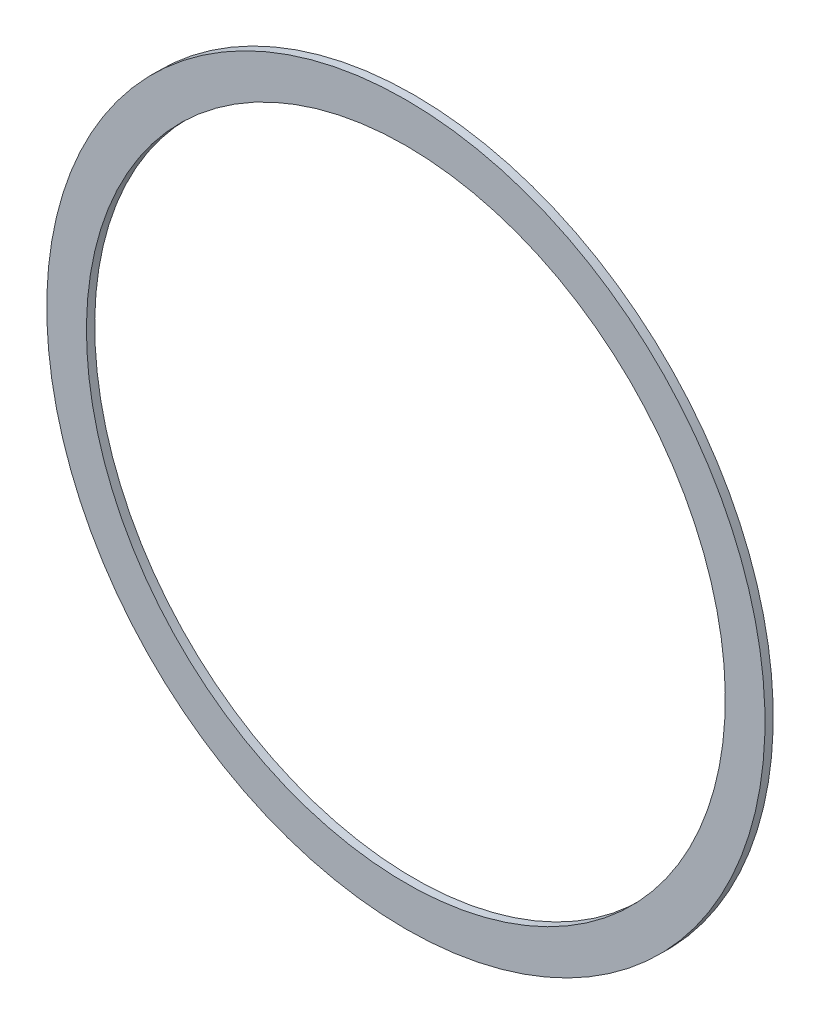
SolidWorks part; units mm, degrees
material "Balsa"
ref_plane "Front Plane" through (0, 0, 0) normal (0, 0, 1) x (1, 0, 0)
ref_plane "Top Plane" through (0, 0, 0) normal (0, 1, 0) x (1, 0, 0)
ref_plane "Right Plane" through (0, 0, 0) normal (1, 0, 0) x (0, 0, -1)
sketch "Sketch1" plane through (0, 0, 0) normal (0, 0, 1) x (1, 0, 0)
  line L0 (0, 0) -> (0, 499.9473) construction
  line L1 (0, -114.7984) -> (0, -129.4545) construction
  line L2 (0, -374.4718) -> (0, 404.2655) construction
  line L3 (-1.651, 142.9921) -> (-1.651, 150.6121) construction
  line L4 (1.651, 142.9921) -> (1.651, 150.6121) construction
  line L5 (-1.651, 142.9921) -> (1.651, 142.9921) construction
  line L6 (136.2041, -53.806) -> (0.0002, 24.7625) construction
  line L7 (-136.2076, -53.7991) -> (0.0002, 24.7625) construction
  line L8 (136.2041, -53.806) -> (0.0002, 24.7625) construction
  line L9 (-136.2076, -53.7991) -> (0.0002, 24.7625) construction
  line L10 (-125.0584, -45.4626) -> (-118.4576, -41.6554) construction
  line L11 (-123.6259, -48.4483) -> (-116.8078, -44.5157) construction
  line L12 (-118.4576, -41.6554) -> (-116.8078, -44.5157) construction
  line L13 (-124.1455, -48.7479) -> (-123.6847, -48.4822) construction
  line L14 (-123.6847, -48.4822) -> (-123.6259, -48.4483) construction
  line L15 (-125.7952, -45.8876) -> (-125.1113, -45.4931) construction
  line L16 (-125.1113, -45.4931) -> (-125.0584, -45.4626) construction
  line L17 (125.4797, -45.7137) -> (125.1075, -45.499) construction
  line L18 (123.8298, -48.5739) -> (123.6807, -48.488) construction
  line L19 (117.0223, -44.647) -> (118.6722, -41.7868) construction
  line L20 (123.6807, -48.488) -> (123.6228, -48.4545) construction
  line L21 (123.6228, -48.4545) -> (117.0223, -44.647) construction
  line L22 (125.1075, -45.499) -> (125.0554, -45.4689) construction
  line L23 (125.0554, -45.4689) -> (118.6722, -41.7868) construction
  line L24 (-107.079, -46.8884) -> (-120.3798, -54.5735)
  line L25 (-108.6638, -44.1348) -> (-121.9647, -51.8199)
  line L28 (-115.4206, -47.9666) -> (-121.9445, -51.7361) construction
  line L29 (-120.2754, -54.5131) -> (-108.646, -44.1245) construction
  line L30 (-114.4607, -49.3188) -> (-122.1124, -53.7399) construction
  line L31 (-113.7686, -50.8257) -> (-120.3665, -54.6379) construction
  line L32 (-115.4206, -47.9666) -> (-113.7686, -50.8257) construction
  line L33 (107.3025, -47.0245) -> (129.9098, -60.0883)
  line L34 (108.8884, -44.2715) -> (131.505, -57.3407)
  line L35 (129.9098, -60.0883) -> (131.505, -57.3407)
  line L36 (129.9098, -60.0883) -> (131.505, -57.3407) construction
  line L37 (108.8884, -44.2715) -> (131.505, -57.3407) construction
  line L38 (107.3025, -47.0245) -> (129.9098, -60.0883) construction
  line L39 (129.9098, -60.0883) -> (108.8884, -44.2715) construction
  line L40 (119.3991, -52.1799) -> (101.8722, -42.0519) construction
  line L41 (120.3631, -54.6438) -> (113.7655, -50.8313)
  line L42 (122.0152, -51.7848) -> (122.0057, -51.7794) construction
  line L43 (113.7655, -50.8313) -> (115.4176, -47.9723)
  line L44 (122.0057, -51.7794) -> (121.9413, -51.7421) construction
  line L45 (121.9413, -51.7421) -> (115.4176, -47.9723)
  line L46 (-108.6638, -44.1348) -> (-121.9647, -51.8199)
  line L47 (-107.079, -46.8884) -> (-120.3798, -54.5735)
  arc A0 (-1.651, 150.6121) -> (-125.0584, -45.4626) centre (0, 12.7) ccw
  circle A1 centre (0, 12.7) radius 120.904
  arc A2 (0, 150.622) -> (-1.651, 150.6121) centre (0, 12.7) ccw
  circle A3 centre (0, 12.7) radius 137.922 construction
  arc A4 (1.651, 150.6121) -> (0, 150.622) centre (0, 12.7) ccw
  arc A5 (-124.3508, -46.9604) -> (-123.6259, -48.4483) centre (0, 12.7) ccw
  arc A6 (-123.6259, -48.4483) -> (-121.9445, -51.7361) centre (0, 12.7) ccw
  arc A7 (-125.0584, -45.4626) -> (-124.3508, -46.9604) centre (0, 12.7) ccw
  arc A8 (124.3477, -46.9667) -> (125.0554, -45.4689) centre (0, 12.7) ccw
  arc A9 (125.0554, -45.4689) -> (1.651, 150.6121) centre (0, 12.7) ccw
  arc A10 (123.6228, -48.4545) -> (124.3477, -46.9667) centre (0, 12.7) ccw
  arc A11 (-121.9153, -51.7914) -> (-121.1641, -53.1919) centre (0, 12.7) ccw
  arc A12 (-120.3665, -54.6379) -> (120.3631, -54.6438) centre (0, 12.7) ccw
  arc A13 (-121.9445, -51.7361) -> (-121.9153, -51.7914) centre (0, 12.7) ccw
  arc A14 (-121.1641, -53.1919) -> (-120.3827, -54.6089) centre (0, 12.7) ccw
  arc A15 (-120.3827, -54.6089) -> (-120.397, -54.5834) centre (0, 12.7) ccw construction
  arc A16 (-120.397, -54.5834) -> (-120.3665, -54.6379) centre (0, 12.7) ccw construction
  arc A17 (120.3936, -54.5893) -> (121.0419, -53.416) centre (0, 12.7) ccw construction
  arc A18 (121.9413, -51.7421) -> (123.6228, -48.4545) centre (0, 12.7) ccw
  arc A19 (120.3631, -54.6438) -> (120.3936, -54.5893) centre (0, 12.7) ccw construction
  arc A20 (121.0419, -53.416) -> (121.9121, -51.7974) centre (0, 12.7) ccw construction
  arc A21 (121.9121, -51.7974) -> (121.9413, -51.7421) centre (0, 12.7) ccw construction
  spline S0 degree 3 poles (-891.8479, -1778.6566) (-223.5651, -622.3771) (442.5776, 534.0478) (1105.5233, 1688.7852) knots -629.037343 -629.037343 -629.037343 -629.037343 630.975162 630.975162 630.975162 630.975162 weights 1.000396 0.999868 0.999868 1.000397 only from (107.3025, -47.0245) to (108.8884, -44.2715)
  spline S1 degree 3 poles (-66.0123, 133.6164) (-70.0128, 131.4329) (-73.8716, 129.0699) (-81.3156, 123.9975) (-84.9009, 121.288) (-91.7995, 115.5249) (-95.113, 112.4712) (-99.0811, 108.4341) (-99.866, 107.6157) (-101.4182, 105.9565) (-102.1865, 105.1147) (-104.4569, 102.5643) (-105.9223, 100.8334) (-110.1768, 95.5512) (-115.4725, 88.2691) (-120.0285, 80.5179) (-123.1654, 74.5269) (-124.1643, 72.5002) (-125.5914, 69.415) (-126.0551, 68.3791) (-126.9587, 66.292) (-127.3989, 65.2397) (-129.5278, 59.9684) (-131.0098, 55.7) (-133.5456, 47.0638) (-134.5993, 42.696) (-136.2795, 33.8613) (-136.906, 29.3944) (-137.415, 23.7472) (-137.5031, 22.6146) (-137.6514, 20.3429) (-137.7116, 19.2049) (-137.8496, 15.7999) (-137.8852, 13.5361) (-137.8263, 6.7629) (-137.3062, -2.2197) (-135.9163, -11.1068) (-134.5433, -17.7359) (-134.0304, -19.9395) (-132.8922, -24.3345) (-132.2653, -26.5303) (-130.2347, -33.03) (-128.6774, -37.2656) (-126.1245, -43.2881) (-125.286, -45.1501) (-124.4066, -46.9926) knots 0 0 0 0 0.03125 0.03125 0.0625 0.0625 0.09375 0.09375 0.101563 0.101563 0.109375 0.109375 0.125 0.125 0.15625 0.1875 0.1875 0.203125 0.203125 0.210938 0.210938 0.21875 0.21875 0.25 0.25 0.28125 0.28125 0.3125 0.3125 0.320313 0.320313 0.328125 0.328125 0.34375 0.34375 0.375 0.40625 0.40625 0.421875 0.421875 0.4375 0.4375 0.46875 0.46875 0.48295 0.48295 0.48295 0.48295 construction
  spline S2 degree 3 poles (-1557.5256, 1030.3086) (-495.2142, -0.1753) (-82.1366, -210.7146) (81.4542, -98.9353) (85.033, -96.2237) (91.9188, -90.4573) (95.2258, -87.4025) (99.1858, -83.3647) (99.9691, -82.5461) (101.5182, -80.8868) (102.2849, -80.0449) (104.5506, -77.4941) (106.013, -75.7632) (110.2586, -70.4809) (112.9006, -66.8403) (117.8152, -59.3254) (120.0877, -55.4512) (123.2166, -49.4629) (124.2129, -47.4373) (125.6361, -44.3538) (126.0986, -43.3185) (126.9997, -41.2327) (127.4386, -40.181) (129.5618, -34.9121) (131.0396, -30.646) (133.5674, -22.0152) (134.6173, -17.6505) (136.2906, -8.8227) (136.914, -4.3596) (137.4197, 1.2823) (137.5071, 2.4139) (137.6542, 4.6834) (137.7138, 5.8206) (137.85, 9.2232) (137.8846, 11.4853) (137.8228, 18.2533) (137.2995, 27.2283) (135.9081, 36.1069) (134.5347, 42.7292) (134.0218, 44.9305) (132.8839, 49.3207) (132.2571, 51.5145) (130.2267, 58.0093) (128.67, 62.2416) (125.1615, 70.5162) (123.2097, 74.5586) (118.9108, 82.4534) (116.5637, 86.3058) (113.3753, 90.999) (112.7241, 91.9325) (111.3996, 93.7822) (110.7272, 94.697) (108.6802, 97.4113) (107.2757, 99.181) (102.9447, 104.3725) (96.8571, 110.9816) (90.1513, 116.9722) (84.8861, 121.2292) (83.0917, 122.6088) (80.3399, 124.6181) (79.4113, 125.2786) (77.543, 126.5731) (76.6028, 127.2075) (71.8708, 130.3161) (67.9881, 132.6004) (60.0328, 136.7739) (55.9603, 138.6631) (47.6249, 142.0446) (43.3619, 143.537) (37.9102, 145.1462) (36.8136, 145.4551) (34.6205, 146.0438) (33.5224, 146.3241) (30.2234, 147.1229) (28.0179, 147.5997) (21.3832, 148.8649) (16.9358, 149.4889) (7.993, 150.3014) (3.4975, 150.4899) (-3.2824, 150.4396) (-5.5486, 150.3672) (-10.0934, 150.1088) (-12.3559, 149.9236) (-19.101, 149.2046) (-23.5473, 148.5072) (-32.3412, 146.6856) (-36.6887, 145.5614) (-43.1354, 143.5526) (-45.2718, 142.8291) (-49.5193, 141.273) (-51.6323, 140.4395) (-274.1905, 46.1884) (-224.836, -608.7963) (101.1574, -1839.6029) knots -1.31339 -1.31339 -1.31339 -1.31339 0.03125 0.03125 0.0625 0.0625 0.09375 0.09375 0.101563 0.101563 0.109375 0.109375 0.125 0.125 0.15625 0.15625 0.1875 0.1875 0.203125 0.203125 0.210938 0.210938 0.21875 0.21875 0.25 0.25 0.28125 0.28125 0.3125 0.3125 0.320313 0.320313 0.328125 0.328125 0.34375 0.34375 0.375 0.40625 0.40625 0.421875 0.421875 0.4375 0.4375 0.46875 0.46875 0.5 0.5 0.53125 0.53125 0.539062 0.539062 0.546875 0.546875 0.5625 0.5625 0.59375 0.625 0.625 0.640625 0.640625 0.648437 0.648437 0.65625 0.65625 0.6875 0.6875 0.71875 0.71875 0.75 0.75 0.757812 0.757812 0.765625 0.765625 0.78125 0.78125 0.8125 0.8125 0.84375 0.84375 0.859375 0.859375 0.875 0.875 0.90625 0.90625 0.9375 0.9375 0.953125 0.953125 0.96875 0.96875 2.612134 2.612134 2.612134 2.612134 only from (66.1767, -108.566) to (-66.0123, 133.6164)
  spline S3 degree 3 poles (66.1767, -108.566) (70.1708, -106.3789) (74.0231, -104.0129) (81.4542, -98.9353) (85.033, -96.2237) (91.9188, -90.4573) (95.2258, -87.4025) (99.1858, -83.3647) (99.9691, -82.5461) (101.5182, -80.8868) (102.2849, -80.0449) (104.5506, -77.4941) (106.013, -75.7632) (110.2586, -70.4809) (112.9006, -66.8403) (117.8152, -59.3254) (120.0877, -55.4512) (123.2166, -49.4629) (124.2129, -47.4373) (125.6361, -44.3538) (126.0986, -43.3185) (126.9997, -41.2327) (127.4386, -40.181) (129.5618, -34.9121) (131.0396, -30.646) (133.5674, -22.0152) (134.6173, -17.6505) (136.2906, -8.8227) (136.914, -4.3596) (137.4197, 1.2823) (137.5071, 2.4139) (137.6542, 4.6834) (137.7138, 5.8206) (137.85, 9.2232) (137.8846, 11.4853) (137.8228, 18.2533) (137.2995, 27.2283) (135.9081, 36.1069) (134.5347, 42.7292) (134.0218, 44.9305) (132.8839, 49.3207) (132.2571, 51.5145) (130.2267, 58.0093) (128.67, 62.2416) (125.1615, 70.5162) (123.2097, 74.5586) (118.9108, 82.4534) (116.5637, 86.3058) (113.3753, 90.999) (112.7241, 91.9325) (111.3996, 93.7822) (110.7272, 94.697) (108.6802, 97.4113) (107.2757, 99.181) (102.9447, 104.3725) (96.8571, 110.9816) (90.1513, 116.9722) (84.8861, 121.2292) (83.0917, 122.6088) (80.3399, 124.6181) (79.4113, 125.2786) (77.543, 126.5731) (76.6028, 127.2075) (71.8708, 130.3161) (67.9881, 132.6004) (60.0328, 136.7739) (55.9603, 138.6631) (47.6249, 142.0446) (43.3619, 143.537) (37.9102, 145.1462) (36.8136, 145.4551) (34.6205, 146.0438) (33.5224, 146.3241) (30.2234, 147.1229) (28.0179, 147.5997) (21.3832, 148.8649) (16.9358, 149.4889) (7.993, 150.3014) (3.4975, 150.4899) (-3.2824, 150.4396) (-5.5486, 150.3672) (-10.0934, 150.1088) (-12.3559, 149.9236) (-19.101, 149.2046) (-23.5473, 148.5072) (-32.3412, 146.6856) (-36.6887, 145.5614) (-43.1354, 143.5526) (-45.2718, 142.8291) (-49.5193, 141.273) (-51.6323, 140.4395) (-57.9206, 137.7764) (-62.0153, 135.798) (-66.0123, 133.6164) knots 0 0 0 0 0.03125 0.03125 0.0625 0.0625 0.09375 0.09375 0.101563 0.101563 0.109375 0.109375 0.125 0.125 0.15625 0.15625 0.1875 0.1875 0.203125 0.203125 0.210938 0.210938 0.21875 0.21875 0.25 0.25 0.28125 0.28125 0.3125 0.3125 0.320313 0.320313 0.328125 0.328125 0.34375 0.34375 0.375 0.40625 0.40625 0.421875 0.421875 0.4375 0.4375 0.46875 0.46875 0.5 0.5 0.53125 0.53125 0.539062 0.539062 0.546875 0.546875 0.5625 0.5625 0.59375 0.625 0.625 0.640625 0.640625 0.648437 0.648437 0.65625 0.65625 0.6875 0.6875 0.71875 0.71875 0.75 0.75 0.757812 0.757812 0.765625 0.765625 0.78125 0.78125 0.8125 0.8125 0.84375 0.84375 0.859375 0.859375 0.875 0.875 0.90625 0.90625 0.9375 0.9375 0.953125 0.953125 0.96875 0.96875 1 1 1 1 construction
  spline S4 degree 3 poles (-124.4066, -46.9926) (-124.169, -47.4906) (-123.9283, -47.9871) (-123.6847, -48.4822) knots 0.48295 0.48295 0.48295 0.48295 0.486788 0.486788 0.486788 0.486788 construction
  spline S5 degree 3 poles (-123.6847, -48.4822) (-122.846, -50.1865) (-121.9718, -51.874) (-118.9108, -57.4955) (-116.5612, -61.3517) (-113.369, -66.0497) (-112.7169, -66.9844) (-111.3913, -68.8351) (-110.7184, -69.7503) (-108.6697, -72.4662) (-107.264, -74.2369) (-102.929, -79.4315) (-96.8353, -86.0447) (-90.1214, -92.0392) (-84.8493, -96.299) (-83.0524, -97.6795) (-80.2967, -99.6899) (-79.367, -100.3507) (-77.4971, -101.6451) (-76.5559, -102.2795) (-71.8198, -105.3881) (-67.9332, -107.6723) (-59.9695, -111.8452) (-55.8924, -113.7339) (-47.5468, -117.114) (-43.2782, -118.6053) (-37.8188, -120.2127) (-36.7216, -120.521) (-34.5268, -121.1085) (-33.4279, -121.3881) (-30.1264, -122.185) (-27.9191, -122.6605) (-21.2788, -123.9216) (-16.8274, -124.5426) (-7.8757, -125.3484) (-3.3755, -125.5332) (3.4122, -125.4766) (5.6812, -125.4019) (10.231, -125.1387) (12.493, -124.9512) (19.2413, -124.2249) (23.6899, -123.5224) (32.4889, -121.6898) (36.8393, -120.5597) (43.2904, -118.5412) (45.4283, -117.8143) (48.6163, -116.6419) (49.6759, -116.2374) (51.7885, -115.4006) (52.8426, -114.968) (58.0839, -112.7404) (62.1792, -110.755) (66.1767, -108.566) knots 0.486788 0.486788 0.486788 0.486788 0.5 0.5 0.53125 0.53125 0.539062 0.539062 0.546875 0.546875 0.5625 0.5625 0.59375 0.625 0.625 0.640625 0.640625 0.648437 0.648437 0.65625 0.65625 0.6875 0.6875 0.71875 0.71875 0.75 0.75 0.757812 0.757812 0.765625 0.765625 0.78125 0.78125 0.8125 0.8125 0.84375 0.84375 0.859375 0.859375 0.875 0.875 0.90625 0.90625 0.9375 0.9375 0.953125 0.953125 0.960937 0.960937 0.96875 0.96875 1 1 1 1 construction
  spline S6 degree 3 poles (-108.6638, -44.1348) (-108.1355, -45.0527) (-107.6073, -45.9705) (-107.079, -46.8884) knots 0 0 0 0 1 1 1 1 weights 1 1 1 1
  spline S7 degree 3 poles (-121.9647, -51.8199) (-121.4364, -52.7377) (-120.9081, -53.6556) (-120.3798, -54.5735) knots 0 0 0 0 1 1 1 1 weights 1 1 1 1
  spline S9 degree 3 poles (-121.8597, -51.7592) (-121.5957, -52.2182) (-121.3316, -52.6772) (-121.0676, -53.1362) knots 0 0 0 0 0.5 0.5 0.5 0.5 weights 1 1 1 1 construction
  spline S11 degree 3 poles (107.3025, -47.0245) (107.8311, -46.1069) (108.3597, -45.1892) (108.8884, -44.2715) knots 0 0 0 0 1 1 1 1 weights 1 1 1 1
  spline S12 degree 3 poles (-1117.6926, 1681.4946) (-455.9021, 527.2867) (209.8433, -629.4163) (878.1921, -1786.2645) knots -630.157908 -630.157908 -630.157908 -630.157908 629.848871 629.848871 629.848871 629.848871 weights 1.000509 0.999831 0.99983 1.000507 only from (-121.9647, -51.8199) to (-120.3798, -54.5735)
  spline S13 degree 3 poles (-1104.4721, 1689.253) (-442.507, 534.8951) (223.2028, -621.8101) (891.4356, -1778.7423) knots -630.135261 -630.135261 -630.135261 -630.135261 629.876801 629.876801 629.876801 629.876801 weights 1.000459 0.999847 0.999847 1.000457 only from (-108.6638, -44.1348) to (-107.079, -46.8884)
  point P7 (0, -125.5003)
  point P8 (0, 150.4602)
  point P25 (-125.0584, -45.4626)
  point P38 (123.6228, -48.4545)
  dimension "D2" = 275.844
  dimension "D1" = 275.9605
  dimension "D3" = 12.7
  dimension "D5" = 3.302
  dimension "D6" = 7.62
  dimension "D7" = 3.302
  dimension "D8" = 7.62
  dimension "D9" = 3.302
  dimension "D10" = 7.62
  dimension "D11" = 3.302
  dimension "D12" = 7.62
  dimension "D13" = 3.302
  dimension "D14" = 7.62
  dimension "D4" = 17.018
extrude "Boss-Extrude1" [suppressed] add sketch "Sketch1" along normal mid plane 3.175
sketch "Sketch2" plane through (248.2736, -245.0135, 0) normal (0, 0, -1) x (0, -1, 0)
  line L3 (-245.0135, 248.2736) -> (-427.6569, 248.2736) construction
  circle A1 centre (-257.7135, 248.2736) radius 137.922
  circle A16 centre (-257.7135, 248.2736) radius 122.682
  dimension "D1" = 12.7
  dimension "D2" = 275.844
  dimension "D3" = 15.24
fillet "Fillet1" [suppressed] radius 1.27
extrude "Boss-Extrude2" add sketch "Sketch2" along normal mid plane 3.175
equation "\"slotwidth\"=0.13"
equation "\"D11@Sketch1\"=\"slotwidth\""
